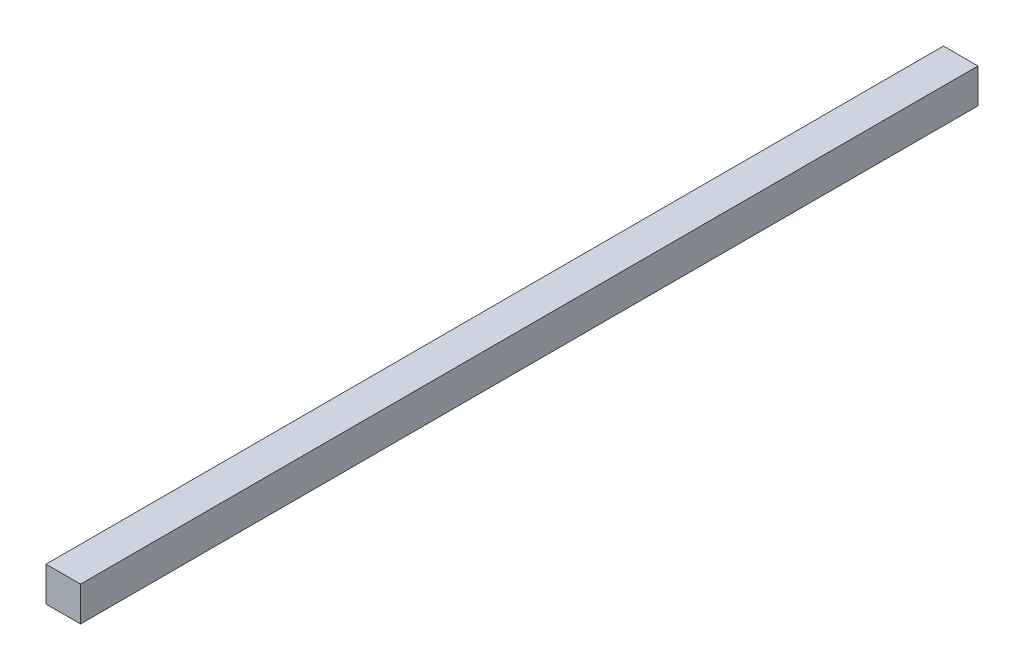
SolidWorks part; units mm, degrees
ref_plane "Front Plane" through (0, 0, 0) normal (0, 0, 1) x (1, 0, 0)
ref_plane "Top Plane" through (0, 0, 0) normal (0, 1, 0) x (1, 0, 0)
ref_plane "Right Plane" through (0, 0, 0) normal (1, 0, 0) x (0, 0, -1)
sketch "Sketch1" plane through (0, 0, 0) normal (0, 1, 0) x (1, 0, 0)
  line L1 (0, 0) -> (25.4, 0)
  line L2 (0, 0) -> (0, 660.4)
  line L3 (0, 660.4) -> (25.4, 660.4)
  line L4 (25.4, 0) -> (25.4, 660.4)
  dimension "D1" = 660.4
  dimension "D2" = 25.4
extrude "Boss-Extrude1" add sketch "Sketch1" along normal blind 25.4
